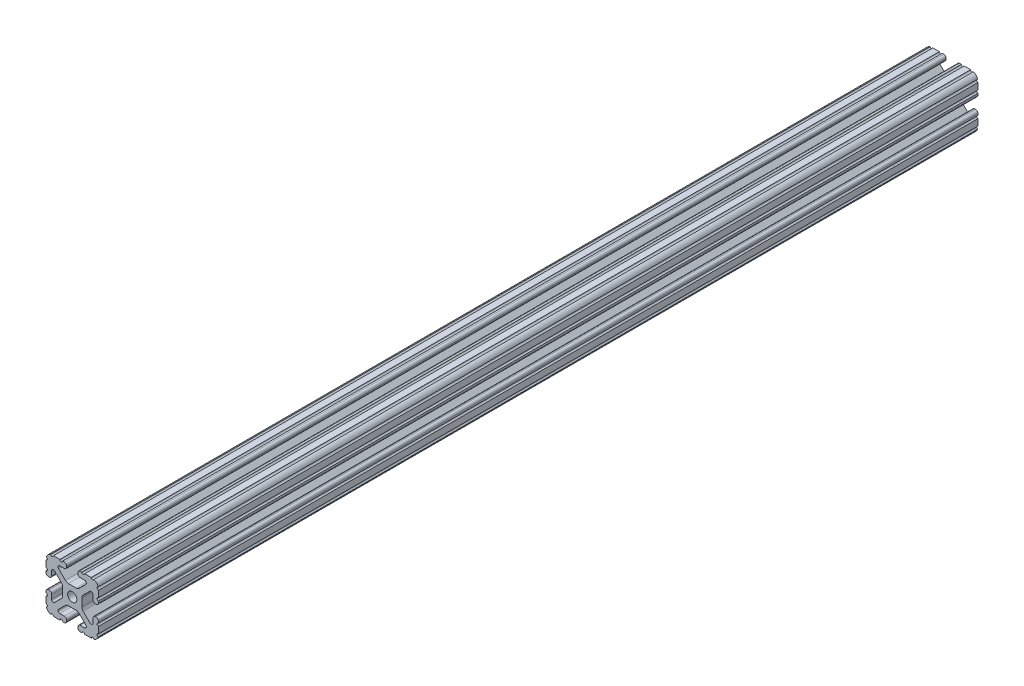
SolidWorks part; units mm, degrees
ref_plane "Front Plane" through (0, 0, 0) normal (0, 0, 1) x (1, 0, 0)
ref_plane "Top Plane" through (0, 0, 0) normal (0, 1, 0) x (1, 0, 0)
ref_plane "Right Plane" through (0, 0, 0) normal (1, 0, 0) x (0, 0, -1)
sketch "Sketch2" plane through (0, 0, 0) normal (0, 0, 1) x (1, 0, 0)
  line L0 (0, 19.05) -> (0, -19.05) construction
  line L1 (-19.05, 0) -> (19.05, 0) construction
  line L2 (4.064, -19.05) -> (19.05, -19.05)
  line L3 (19.05, -19.05) -> (19.05, -4.064)
  line L4 (4.064, -19.05) -> (4.064, -14.986)
  line L5 (4.064, -14.986) -> (12.1123, -14.986)
  line L6 (12.1123, -14.986) -> (4.1113, -6.985)
  line L7 (0, 0) -> (19.05, -19.05) construction
  line L8 (19.05, -4.064) -> (14.986, -4.064)
  line L9 (14.986, -4.064) -> (14.986, -12.1123)
  line L10 (14.986, -12.1123) -> (6.985, -4.1113)
  circle A0 centre (0, 0) radius 3.3274
  arc A1 (8.9963, -14.986) -> (9.909, -12.7826) centre (8.9963, -13.6953) ccw construction
  point P8 (0, -6.985)
  dimension "Center Hole Diameter" = 6.6548
  dimension "Rail Height" = 38.1
  dimension "Rail Width" = 38.1
  dimension "T-Slot Width" = 8.128
  dimension "Slot Inner Width" = 20.574
  dimension "Thickness" = 4.064
  dimension "Slot Depth" = 8.001
  dimension "D1" = 4.064
sketch "Sketch3" plane through (0, 0, 0) normal (1, 0, 0) x (0, 0, -1)
  line L0 (-319.151, -19.05) -> (319.151, -19.05) construction
  line L1 (-293.751, 0) -> (293.751, 0) construction
  dimension "Length" = 638.302
  dimension "D1" = 25.4
sketch "Sketch4" plane through (0, 0, 0) normal (0, 0, 1) x (1, 0, 0)
  line L0 (5.7912, -19.05) -> (14.3002, -19.05)
  line L1 (4.064, -19.05) -> (19.05, -19.05) construction
  line L2 (4.064, -19.05) -> (4.064, -14.986) construction
  line L3 (4.064, -14.986) -> (12.1123, -14.986) construction
  line L4 (4.064, -16.7132) -> (4.064, -17.3228)
  line L5 (5.7912, -14.986) -> (8.9963, -14.986)
  line L6 (0, -6.985) -> (2.833, -6.985)
  line L7 (12.1123, -14.986) -> (4.1113, -6.985) construction
  line L8 (5.0152, -7.8889) -> (9.909, -12.7826)
  line L9 (19.05, -19.05) -> (19.05, -4.064) construction
  line L10 (14.986, -12.1123) -> (6.985, -4.1113) construction
  line L11 (14.986, -4.064) -> (14.986, -12.1123) construction
  line L12 (14.986, -8.9963) -> (14.986, -5.7912)
  line L13 (19.05, -4.064) -> (14.986, -4.064) construction
  line L14 (16.7132, -4.064) -> (17.3228, -4.064)
  line L15 (19.05, -5.7912) -> (19.05, -14.3002)
  line L16 (12.7826, -9.909) -> (7.8889, -5.0152)
  line L17 (6.985, 0) -> (6.985, -2.833)
  line L18 (-19.05, 0) -> (19.05, 0) construction
  line L19 (0, -6.985) -> (0, -3.3274)
  line L20 (0, 19.05) -> (0, -19.05) construction
  line L21 (6.985, 0) -> (3.3274, 0)
  arc A0 (4.064, -17.3228) -> (5.7912, -19.05) centre (5.7912, -17.3228) ccw
  arc A2 (4.064, -16.7132) -> (5.7912, -14.986) centre (5.7912, -16.7132) cw
  arc A3 (8.9963, -14.986) -> (9.909, -12.7826) centre (8.9963, -13.6953) ccw
  arc A4 (2.833, -6.985) -> (5.0152, -7.8889) centre (2.833, -10.0711) cw
  arc A5 (14.3002, -19.05) -> (19.05, -14.3002) centre (14.3002, -14.3002) ccw
  arc A6 (12.7826, -9.909) -> (14.986, -8.9963) centre (13.6953, -8.9963) ccw
  arc A7 (14.986, -5.7912) -> (16.7132, -4.064) centre (16.7132, -5.7912) cw
  arc A8 (17.3228, -4.064) -> (19.05, -5.7912) centre (17.3228, -5.7912) cw
  arc A9 (7.8889, -5.0152) -> (6.985, -2.833) centre (10.0711, -2.833) cw
  circle A10 centre (0, 0) radius 3.3274 construction
  arc A11 (0, -3.3274) -> (3.3274, 0) centre (0, 0) ccw
  dimension "D1" = 4.7498
  dimension "D2" = 3.0861
  dimension "D3" = 1.7272
extrude "Boss-Extrude1" add sketch "Sketch4" along normal mid plane 638.302
sketch "Sketch5" plane through (0, 0, 0) normal (0, 0, 1) x (1, 0, 0)
  line L0 (4.064, -19.05) -> (19.05, -19.05) construction
  line L1 (5.7912, -14.986) -> (8.9963, -14.986) construction
  line L3 (0, 0) -> (19.05, -19.05) construction
  line L4 (8.9963, -14.986) -> (8.9963, -19.05) construction
  line L5 (12.1123, -14.986) -> (4.1113, -6.985) construction
  circle A0 centre (14.7395, -19.05) radius 1.016
  circle A1 centre (7.9803, -19.05) radius 1.016
  circle A2 centre (19.05, -14.7395) radius 1.016
  circle A3 centre (19.05, -7.9803) radius 1.016
  point P10 (7.3938, -14.986)
  point P12 (13.6953, -8.9963)
  dimension "D1" = 2.032
extrude "Cut-Extrude1" cut sketch "Sketch5" against normal through all both and the other way through all
mirror "Mirror1" about plane through (0, 0, 0) normal (1, 0, 0) of bodies 137 134
mirror "Mirror2" about plane through (0, 0, 0) normal (0, 1, 0) of bodies 135
equation "\"D1@Boss-Extrude1\"=\"Length@Sketch3\""
equation "\"D1@Sketch2\"=\"Thickness@Sketch2\""
equation "\"D2@Sketch4\"=\"Slot Inner Width@Sketch2\"*0.15"
equation "\"D1@Sketch4\"=\"D3@Sketch4\"*2.75"
equation "\"D3@Sketch4\"=\"Thickness@Sketch2\"*0.425"
equation "\"D1@Sketch5\"=\"Thickness@Sketch2\"*0.5"
